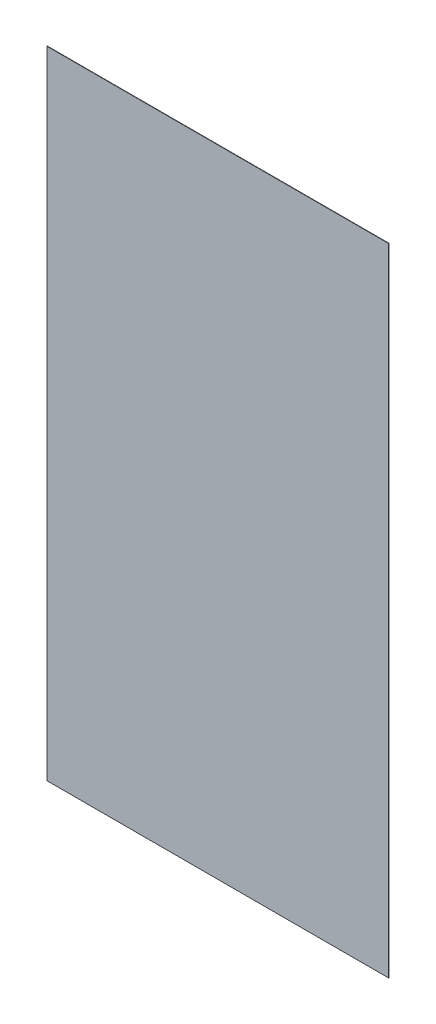
SolidWorks part; units mm, degrees
ref_plane "Front Plane" through (0, 0, 0) normal (0, 0, 1) x (1, 0, 0)
ref_plane "Top Plane" through (0, 0, 0) normal (0, 1, 0) x (1, 0, 0)
ref_plane "Right Plane" through (0, 0, 0) normal (1, 0, 0) x (0, 0, -1)
sketch "Sketch1" plane through (0, 0, 0) normal (0, 0, 1) x (1, 0, 0)
  line L1 (0, 0) -> (873, 0)
  line L2 (0, 0) -> (0, 1625)
  line L3 (0, 1625) -> (873, 1625)
  line L4 (873, 0) -> (873, 1625)
  dimension "D1" = 873
  dimension "D2" = 1625
extrude "Boss-Extrude1" add sketch "Sketch1" along normal blind 1
